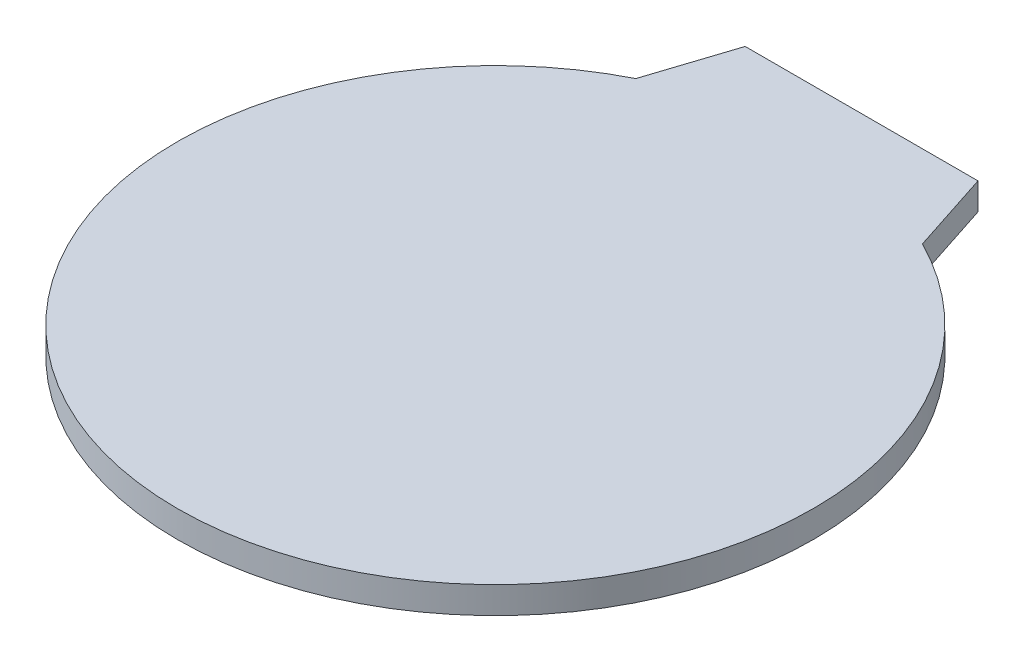
SolidWorks part; units mm, degrees
material "C (Graphite)"
ref_plane "Front Plane" through (0, 0, 0) normal (0, 0, 1) x (1, 0, 0)
ref_plane "Top Plane" through (0, 0, 0) normal (0, 1, 0) x (1, 0, 0)
ref_plane "Right Plane" through (0, 0, 0) normal (1, 0, 0) x (0, 0, -1)
sketch "Sketch1" plane through (0, 0, 0) normal (0, 1, 0) x (1, 0, 0)
  line L0 (0, 17.75) -> (0, 20.45) construction
  line L1 (-6.5, 20.45) -> (6.5, 20.45)
  line L2 (6.5, 20.45) -> (8, 15.845)
  line L3 (-6.5, 20.45) -> (-8, 15.845)
  line L4 (0, 17.75) -> (0, -17.75) construction
  line L5 (-8, 15.845) -> (8, 15.845) construction
  circle A0 centre (0, 0) radius 17.75
  point P8 (0, 20.45)
  dimension "D1" = 35.5
  dimension "D2" = 38.2
  dimension "D3" = 13
  dimension "D4" = 16
extrude "Boss-Extrude2" add sketch "Sketch1" along normal blind 1.5 contours A0 L2 L1 L3 | A0
